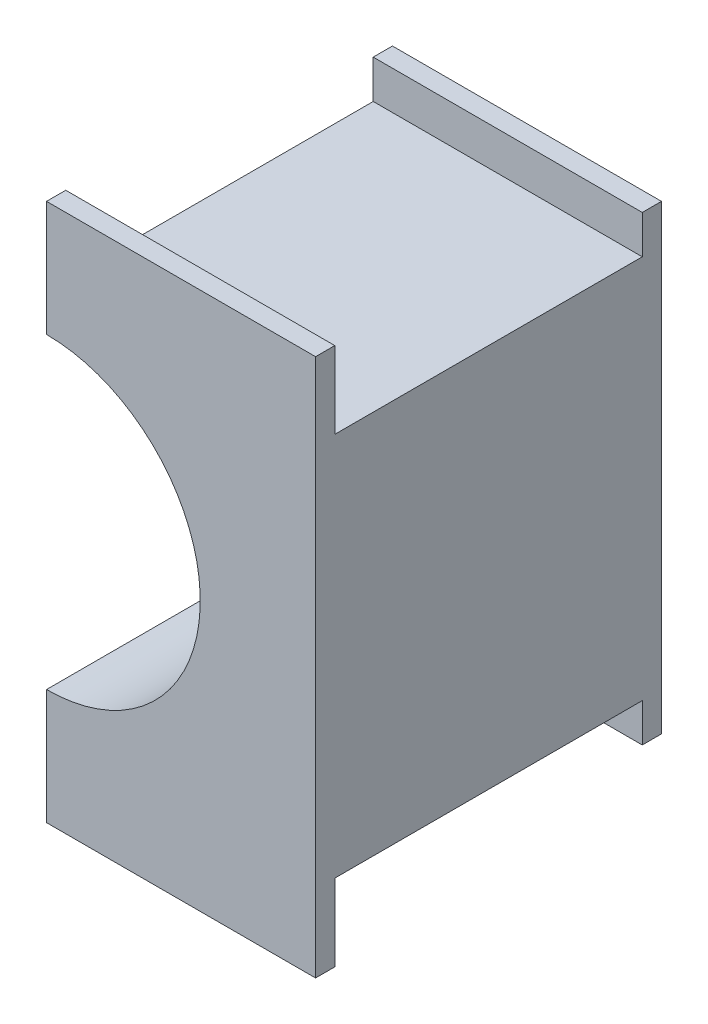
SolidWorks part; units mm, degrees
ref_plane "Plan de face" through (0, 0, 0) normal (0, 0, 1) x (1, 0, 0)
ref_plane "Plan de dessus" through (0, 0, 0) normal (0, 1, 0) x (1, 0, 0)
ref_plane "Plan de droite" through (0, 0, 0) normal (1, 0, 0) x (0, 0, -1)
sketch "Esquisse1" plane through (0, 0, 0) normal (0, 0, 1) x (1, 0, 0)
  line L1 (-2.5, 3.5) -> (1, 3.5)
  line L2 (-2.5, 3.5) -> (-2.5, -3.5)
  line L3 (-2.5, -3.5) -> (1, -3.5)
  line L4 (1, 3.5) -> (1, -3.5)
  arc A0 (-2.5, -2) -> (-2.5, 2) centre (-2.5, 0) ccw
  dimension "D5" = 2
  dimension "D1" = 3.5
  dimension "D2" = 3.5
  dimension "D3" = 7
  dimension "D4" = 2.5
extrude "Boss.-Extru.1" add sketch "Esquisse1" along normal blind 4.5 contours A0 L2 L3 L4 L1
sketch "Esquisse2" plane through (-2.5, 0, 0) normal (-1, 0, 0) x (0, 0, 1)
  line L0 (0, 3.5) -> (0, 2) construction
  line L1 (0, 3.5) -> (4.25, 3.5)
  line L2 (0, 3.5) -> (0, 3)
  line L3 (0, 3) -> (4.25, 3)
  line L4 (4.25, 3.5) -> (4.25, 3)
  line L5 (0.25, 3) -> (4.25, 3)
  line L6 (0.25, 3) -> (0.25, 2.5)
  line L7 (0.25, 2.5) -> (4.25, 2.5)
  line L8 (4.25, 3) -> (4.25, 2.5)
  line L9 (-1000, 0) -> (49000, 0) construction
  line L10 (0.25, -2.5) -> (4.25, -2.5)
  line L11 (4.25, -3) -> (4.25, -2.5)
  line L12 (0.25, -3) -> (4.25, -3)
  line L13 (0.25, -3) -> (0.25, -2.5)
  line L14 (0, -3) -> (4.25, -3)
  line L15 (4.25, -3.5) -> (4.25, -3)
  line L16 (0, -3.5) -> (4.25, -3.5)
  line L17 (0, -3.5) -> (0, -3)
  line M9 (0, 3.5) -> (0, 2)
  line M12 (4.5, 3.5) -> (0, 3.5)
  dimension "D1" = 0.5
  dimension "D2" = 4.25
  dimension "D3" = 0.25
  dimension "D4" = 0.5
extrude "Enlèv. mat.-Extru.2" cut sketch "Esquisse2" against normal through all contours L4 L3 M12 M9 | L8 L3 L6 L7 | L13 L12 L11 L10 | L17 L16 L15 L12 L14
equation "\"3.5.00mm\"=10"
